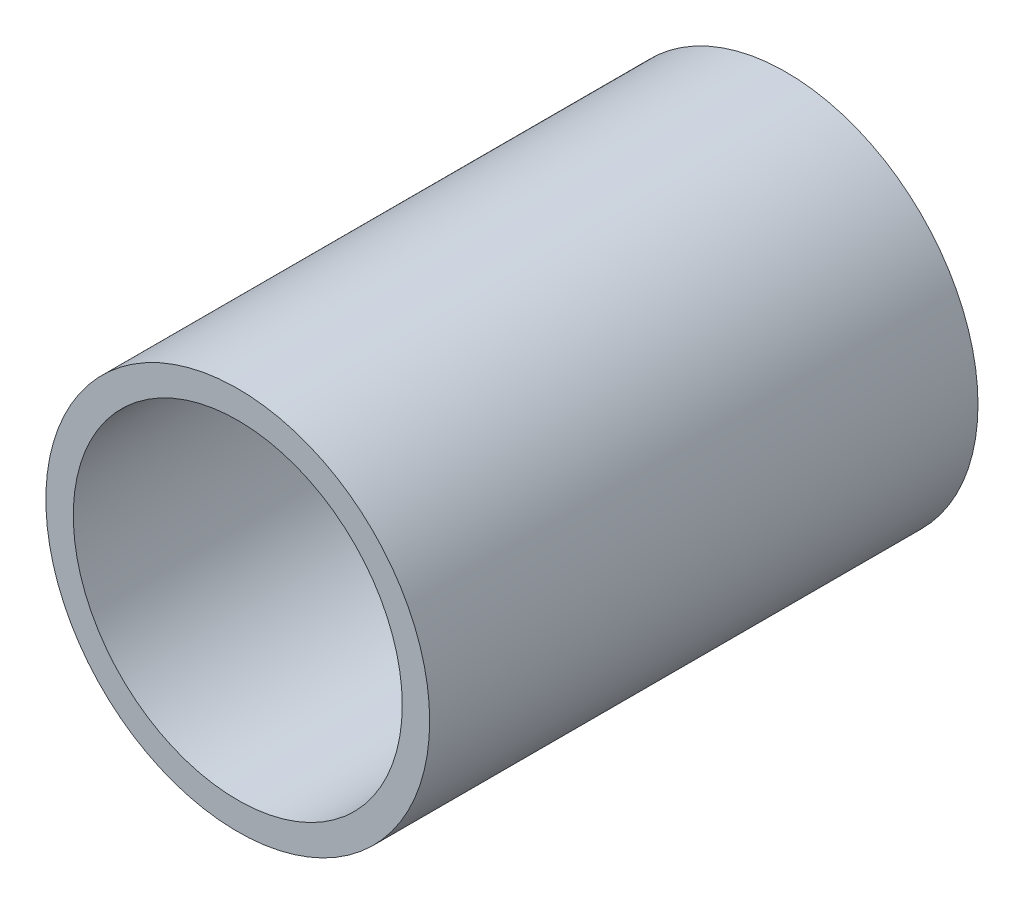
SolidWorks part; units mm, degrees
ref_plane "Front" through (0, 0, 0) normal (0, 0, 1) x (1, 0, 0)
ref_plane "Top" through (0, 0, 0) normal (0, 1, 0) x (1, 0, 0)
ref_plane "Right" through (0, 0, 0) normal (1, 0, 0) x (0, 0, -1)
sketch "Sketch2" plane through (0, 0, 0) normal (0, 0, 1) x (1, 0, 0)
  circle A0 centre (0, 0) radius 8.89
  circle A1 centre (0, 0) radius 7.62
  dimension "D1" = 17.78
  dimension "D2" = 15.24
extrude "Boss-Extrude1" add sketch "Sketch2" along normal blind 25.4
